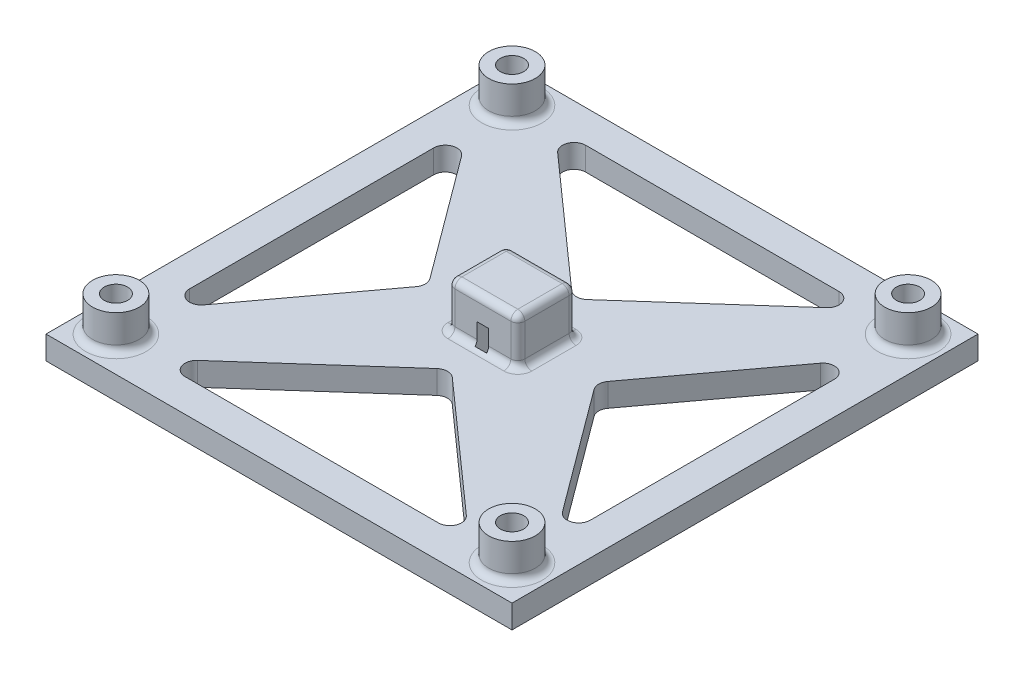
SolidWorks part; units mm, degrees
ref_plane "前基準面" through (0, 0, 0) normal (0, 0, 1) x (1, 0, 0)
ref_plane "上基準面" through (0, 0, 0) normal (0, 1, 0) x (1, 0, 0)
ref_plane "右基準面" through (0, 0, 0) normal (1, 0, 0) x (0, 0, -1)
sketch "草圖1" plane through (0, 0, 0) normal (0, 1, 0) x (1, 0, 0)
  line L0 (-1000, 0) -> (49000, 0) construction
  line L1 (-100, -100) -> (100, -100)
  line L2 (-100, -100) -> (-100, 100)
  line L3 (-100, 100) -> (100, 100)
  line L4 (100, -100) -> (100, 100)
  line L5 (-100, -100) -> (100, 100) construction
  line L6 (-100, 100) -> (100, -100) construction
  line L7 (0, -1000) -> (0, 49000) construction
  circle A0 centre (85, 85) radius 5
  circle A1 centre (-85, 85) radius 5
  circle A2 centre (85, -85) radius 5
  circle A3 centre (-85, -85) radius 5
  point P0 (0, 0)
  dimension "D4" = 10
  dimension "D1" = 200
  dimension "D2" = 200
  dimension "D3" = 15
  dimension "D5" = 15
extrude "填料-伸長1" add sketch "草圖1" along normal blind 7
sketch "草圖2" plane through (0, 7, 0) normal (0, 1, 0) x (1, 0, 0)
  line L0 (-1000, 0) -> (49000, 0) construction
  line L1 (0, -1000) -> (0, 49000) construction
  circle A0 centre (-85, -85) radius 5 construction
  circle A1 centre (85, -85) radius 5 construction
  circle A2 centre (85, 85) radius 5 construction
  circle A3 centre (-85, 85) radius 5 construction
  circle A4 centre (-85, -85) radius 5
  circle A5 centre (85, -85) radius 5
  circle A6 centre (85, 85) radius 5
  circle A7 centre (-85, 85) radius 5
  circle A8 centre (-85, 85) radius 10
  circle A9 centre (85, 85) radius 10
  circle A10 centre (85, -85) radius 10
  circle A11 centre (-85, -85) radius 10
  dimension "D1" = 5
extrude "填料-伸長2" add sketch "草圖2" along normal blind 15
sketch "草圖3" plane through (0, 0, 0) normal (0, -1, 0) x (1, 0, 0)
  line L0 (100, 100) -> (100, -100) construction
  line L1 (100, -100) -> (-100, -100) construction
  line L2 (-100, -100) -> (-100, 100) construction
  line L3 (-100, 100) -> (100, 100) construction
  line L4 (100, 100) -> (100, -100)
  line L5 (100, -100) -> (-100, -100)
  line L6 (-100, -100) -> (-100, 100)
  line L7 (-100, 100) -> (100, 100)
extrude "填料-伸長3" add sketch "草圖3" along normal blind 3
sketch "草圖4" plane through (0, 0, 0) normal (0, 0, 1) x (1, 0, 0)
  line L0 (-100, 7) -> (100, 7) construction
  line L1 (-15, 7) -> (-2.5, 7)
  line L2 (-15, 7) -> (-15, 27)
  line L3 (-15, 27) -> (15, 27)
  line L4 (15, 7) -> (15, 27)
  line L5 (0, 0) -> (0, -20.0426) construction
  line L10 (2.5, 7) -> (15, 7)
  line L11 (-2.5, 7) -> (2.5, 7)
  dimension "D1" = 20
  dimension "D2" = 30
extrude "填料-伸長4" add sketch "草圖4" along normal mid plane 25
fillet "圓角1" radius 3 16 edges at (85, 7, 75) (-85, 7, 75) (-85, 7, -95) (85, 7, -95) (0, 7, -12.5) (-15, 7, 0) (0, 7, 12.5) (15, 7, 0) (15, 17, -12.5) (0, 27, -12.5) (-15, 27, 0) (-15, 17, 12.5) (-15, 17, -12.5) (15, 17, 12.5) (15, 27, 0) (0, 27, 12.5)
sketch "草圖5" plane through (0, 0, 0) normal (1, 0, 0) x (0, 0, -1)
  line L0 (0, 0) -> (0, 35.8235) construction
  line L4 (-16, 16.5721) -> (-8, 16.5721)
  line L5 (8, 16.5721) -> (16, 16.5721)
  arc A0 (-16, 16.5721) -> (16, 16.5721) centre (0, 16.5721) ccw
  arc A2 (-8, 16.5721) -> (8, 16.5721) centre (0, 16.5721) ccw
  arc A3 (-16, 16.5721) -> (16, 16.5721) centre (0, 16.5721) ccw construction
  dimension "D1" = 16
  dimension "D2" = 8
extrude "除料-伸長1" cut sketch "草圖5" against normal mid plane 5
sketch "草圖6" plane through (0, 7, 0) normal (0, 1, 0) x (1, 0, 0)
  line L0 (-1000, 0) -> (49000, 0) construction
  line L1 (0, -1000) -> (0, 49000) construction
  line L2 (-67.5, 85.992) -> (0, 25.992)
  line L3 (0, 25.992) -> (67.5, 85.992)
  line L4 (67.5, 85.992) -> (-67.5, 85.992)
  line L5 (85.992, -67.5) -> (85.992, 67.5)
  line L6 (85.992, 67.5) -> (35.992, 0)
  line L7 (35.992, 0) -> (85.992, -67.5)
  line L8 (-67.5, -85.992) -> (67.5, -85.992)
  line L9 (67.5, -85.992) -> (0, -25.992)
  line L10 (0, -25.992) -> (-67.5, -85.992)
  line L11 (-85.992, 67.5) -> (-85.992, -67.5)
  line L12 (-85.992, -67.5) -> (-35.992, 0)
  line L13 (-35.992, 0) -> (-85.992, 67.5)
  point P20 (0, 0)
  dimension "D1" = 135
  dimension "D2" = 60
  dimension "D3" = 50
  dimension "D4" = 50
extrude "除料-伸長2" cut sketch "草圖6" against normal through all
fillet "圓角2" radius 5 12 edges at (-85.992, 2, 67.5) (-35.992, 2, 0) (-85.992, 2, -67.5) (67.5, 2, 85.992) (-67.5, 2, 85.992) (0, 2, 25.992) (85.992, 2, 67.5) (35.992, 2, 0) (85.992, 2, -67.5) (0, 2, -25.992) (67.5, 2, -85.992) (-67.5, 2, -85.992)
